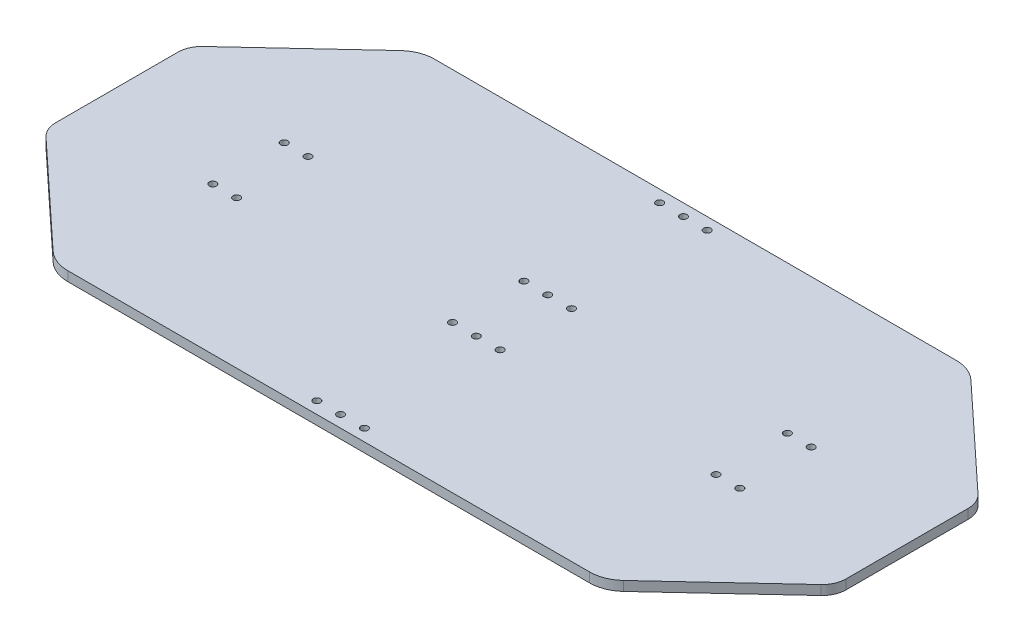
SolidWorks part; units mm, degrees
ref_plane "前视基准面" through (0, 0, 0) normal (0, 0, 1) x (1, 0, 0)
ref_plane "上视基准面" through (0, 0, 0) normal (0, 1, 0) x (1, 0, 0)
ref_plane "右视基准面" through (0, 0, 0) normal (1, 0, 0) x (0, 0, -1)
sketch "草图1" plane through (0, 0, 0) normal (0, 1, 0) x (1, 0, 0)
  line L0 (-119.8191, 72.9803) -> (-162.8128, 32.9663)
  line L1 (-115.5, 77) -> (115.5, 77) construction
  line L2 (-115.5, 77) -> (-115.5, -77) construction
  line L3 (-115.5, -77) -> (115.5, -77) construction
  line L4 (115.5, 77) -> (115.5, -77) construction
  line L5 (-115.5, 77) -> (115.5, -77) construction
  line L6 (-115.5, -77) -> (115.5, 77) construction
  line L7 (-166, 30) -> (166, 30) construction
  line L8 (-166, 30) -> (-166, -30) construction
  line L9 (-166, -30) -> (166, -30) construction
  line L10 (166, 30) -> (166, -30) construction
  line L11 (-166, 30) -> (166, -30) construction
  line L12 (-166, -30) -> (166, 30) construction
  line L13 (-166, 25.6461) -> (-166, -25.6461)
  line L14 (-162.8128, -32.9663) -> (-119.8191, -72.9803)
  line L15 (-109.5998, -77) -> (109.5998, -77)
  line L16 (119.8191, -72.9803) -> (162.8128, -32.9663)
  line L17 (166, -25.6461) -> (166, 25.6461)
  line L18 (162.8128, 32.9663) -> (119.8191, 72.9803)
  line L19 (109.5998, 77) -> (-109.5998, 77)
  arc A0 (119.8191, 72.9803) -> (109.5998, 77) centre (109.5998, 62) ccw
  arc A1 (109.5998, -77) -> (119.8191, -72.9803) centre (109.5998, -62) ccw
  arc A2 (-119.8191, -72.9803) -> (-109.5998, -77) centre (-109.5998, -62) ccw
  arc A3 (-119.8191, 72.9803) -> (-109.5998, 77) centre (-109.5998, 62) cw
  arc A4 (162.8128, -32.9663) -> (166, -25.6461) centre (156, -25.6461) ccw
  arc A5 (166, 25.6461) -> (162.8128, 32.9663) centre (156, 25.6461) ccw
  arc A6 (-166, -25.6461) -> (-162.8128, -32.9663) centre (-156, -25.6461) ccw
  arc A7 (-162.8128, 32.9663) -> (-166, 25.6461) centre (-156, 25.6461) ccw
  point P0 (0, 0)
  point P6 (0, 0)
  dimension "D5" = 15
  dimension "D6" = 10
  dimension "D1" = 154
  dimension "D2" = 231
  dimension "D3" = 332
  dimension "D4" = 60
extrude "凸台-拉伸1" add sketch "草图1" along normal blind 4
sketch "草图3" plane through (0, 4, 0) normal (0, 1, 0) x (1, 0, 0)
  circle A1 centre (10, -72) radius 1.5
  circle A2 centre (0, -72) radius 1.5
  circle A3 centre (-10, -72) radius 1.5
  circle A4 centre (10, -15) radius 1.5
  circle A5 centre (0, -15) radius 1.5
  circle A6 centre (-10, -15) radius 1.5
  circle A7 centre (10, 15) radius 1.5
  circle A8 centre (0, 15) radius 1.5
  circle A9 centre (-10, 15) radius 1.5
  circle A10 centre (10, 72) radius 1.5
  circle A11 centre (0, 72) radius 1.5
  circle A12 centre (-10, 72) radius 1.5
  circle A13 centre (-100.7, 15) radius 1.5
  circle A14 centre (-110.7, 15) radius 1.5
  circle A15 centre (-100.7, -15) radius 1.5
  circle A16 centre (-110.7, -15) radius 1.5
  circle A17 centre (100.7, 15) radius 1.5
  circle A18 centre (110.7, 15) radius 1.5
  circle A19 centre (100.7, -15) radius 1.5
  circle A20 centre (110.7, -15) radius 1.5
  point P58 (-10, 15)
  point P60 (-100.7, 15)
  dimension "D1" = 3
extrude "切除-拉伸1" cut sketch "草图3" against normal through all
